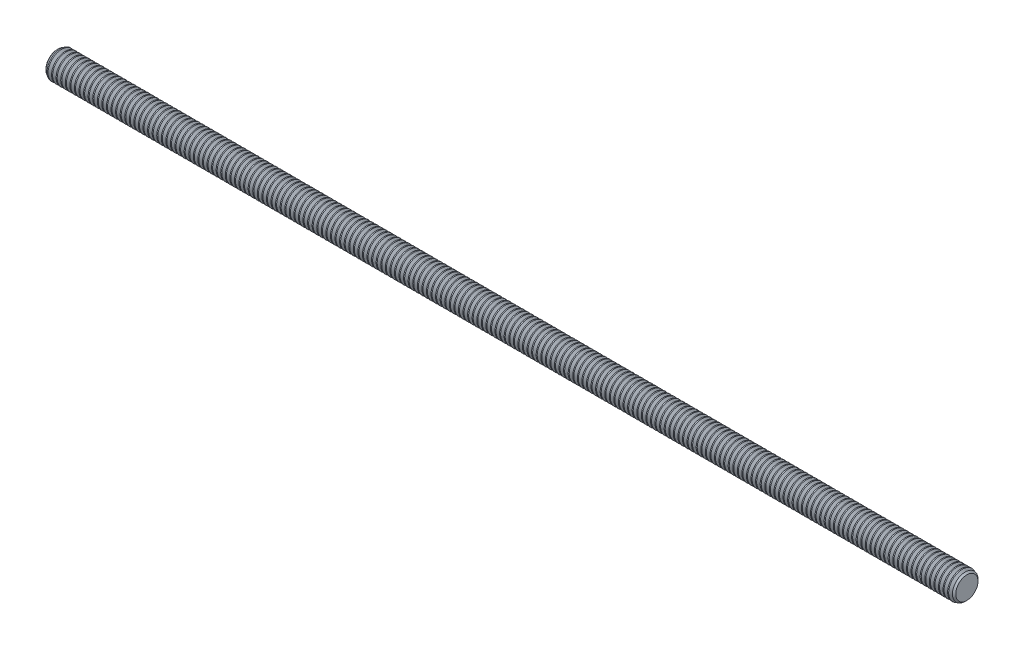
SolidWorks part; units mm, degrees
ref_plane "Plane1" through (0, 0, 0) normal (0, 0, 1) x (1, 0, 0)
ref_plane "Plane2" through (0, 0, 0) normal (0, 1, 0) x (1, 0, 0)
ref_plane "Plane3" through (0, 0, 0) normal (1, 0, 0) x (0, 0, -1)
sketch "BodySke" plane through (0, 0, 0) normal (0, 0, 1) x (1, 0, 0)
  line L0 (195.109, 15.875) -> (195.109, -6.35) construction
  line L1 (1, 15.875) -> (1, -3.175) construction
  line L2 (200, 6.35) -> (200, 3.175) construction
  line L10 (0, 3) -> (200, 3)
  line L12 (200, 3) -> (200, 0)
  line L13 (200, 0) -> (0, 0)
  line L14 (-3.175, 0) -> (107.95, 0) construction
  line L18 (0, 3) -> (0, 0)
  dimension "Diameter" = 6
  dimension "Minor_dia" = 4.891
  dimension "Length" = 200
  dimension "Advance" = 1
  dimension "Thread_max" = 200
revolve "BaseBody" add sketch "BodySke" angle 360 about L14
cosmetic thread "ThreadCosmetic" [suppressed] parameters "Thread_minor"=4.891
chamfer "Chamfer1" distance 0.5545 angle 45 2 edges at (200, 0, 3) (0, 0, 3)
sketch "ThdSchSke" plane through (0, 0, 0) normal (0, 0, 1) x (1, 0, 0)
  line L0 (0.3883, -2.4455) -> (0, -3)
  line L1 (0.3883, -2.4455) -> (0.7765, -3)
  line L2 (0.7765, -3) -> (0.7765, -3.75)
  line L3 (-3.175, 0) -> (5.1513, 0) construction
  line L4 (0, 3) -> (0, -3) construction
  line L5 (0.7765, -3.75) -> (0, -3.75)
  line L6 (0, -3.75) -> (0, -3)
  dimension "Thread_minor" = 4.891
  dimension "Diameter" = 6
  dimension "SideAngle" = 55
  dimension "VeeAngle" = 70
  dimension "Overcut" = 7.5
revolve "ThreadSchematic" cut sketch "ThdSchSke" angle 360 about L3
pattern_linear "ThdSchPat" count 199 spacing 1.005 along (1, 0, 0) of "ThreadSchematic"
equation "\"Thread_minor@ThreadCosmetic\" = \"Minor_dia@BodySke\""
equation "\"Chamfer@Chamfer1\" =  ( \"Diameter@BodySke\" - \"Minor_dia@BodySke\" ) / 2"
equation "\"Thread_minor@ThdSchSke\" = \"Minor_dia@BodySke\""
equation "\"Diameter@ThdSchSke\" = \"Diameter@BodySke\""
equation "\"Overcut@ThdSchSke\" = \"Diameter@BodySke\" * 1.25"
equation "\"Num_threads@ThdSchPat\" = int( (\"Thread_max@BodySke\" - \"Advance@BodySke\" ) / \"Advance@BodySke\" + 0.999 ) + 1"
equation "\"Advance@ThdSchPat\" = \"Thread_max@BodySke\" /  ( \"Num_threads@ThdSchPat\" - 1 ) 'relax it"
equation "\"Num_threads@ThdSchPat\" = \"Num_threads@ThdSchPat\" - sgn( \"Num_threads@ThdSchPat\" - 1 ) '---chamfered tips only---"
